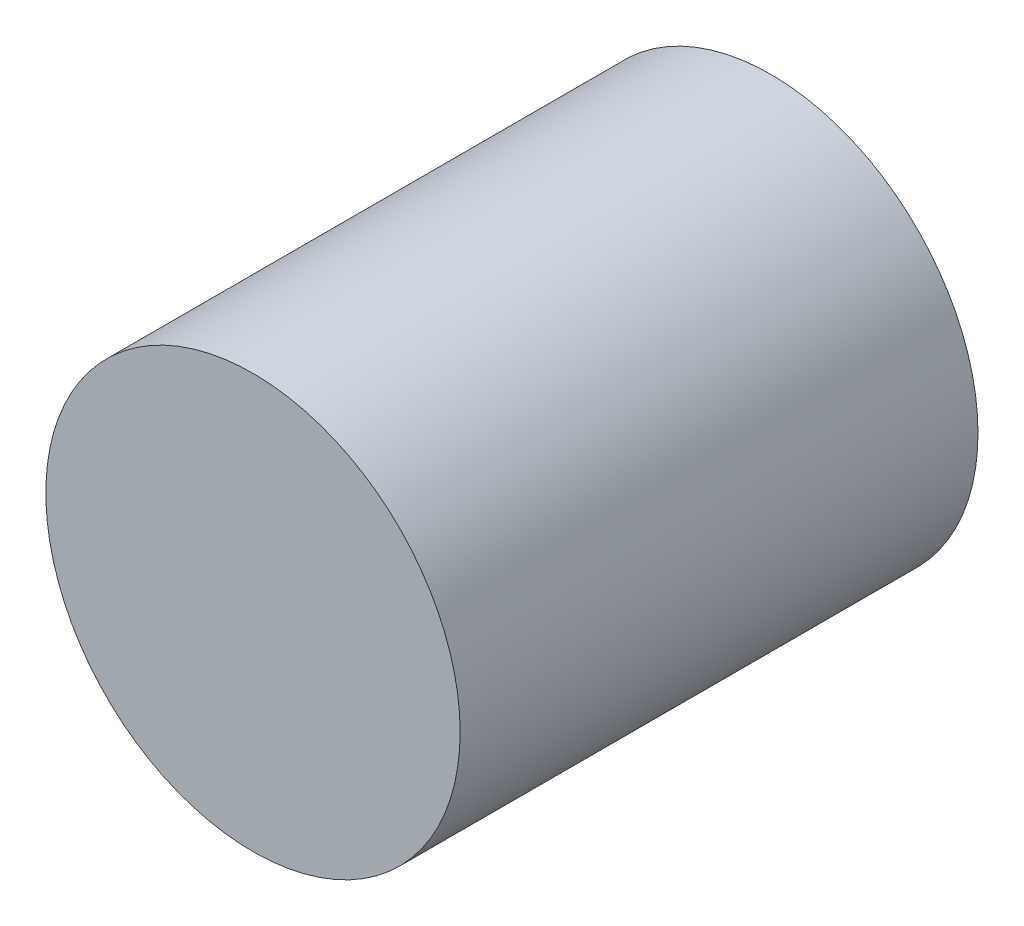
SolidWorks part; units mm, degrees
ref_plane "Front Plane" through (0, 0, 0) normal (0, 0, 1) x (1, 0, 0)
ref_plane "Top Plane" through (0, 0, 0) normal (0, 1, 0) x (1, 0, 0)
ref_plane "Right Plane" through (0, 0, 0) normal (1, 0, 0) x (0, 0, -1)
sketch "Sketch1" plane through (0, 0, 0) normal (0, 0, 1) x (1, 0, 0)
  circle A0 centre (0, 0) radius 6
extrude "Boss-Extrude1" add sketch "Sketch1" along normal blind 15
